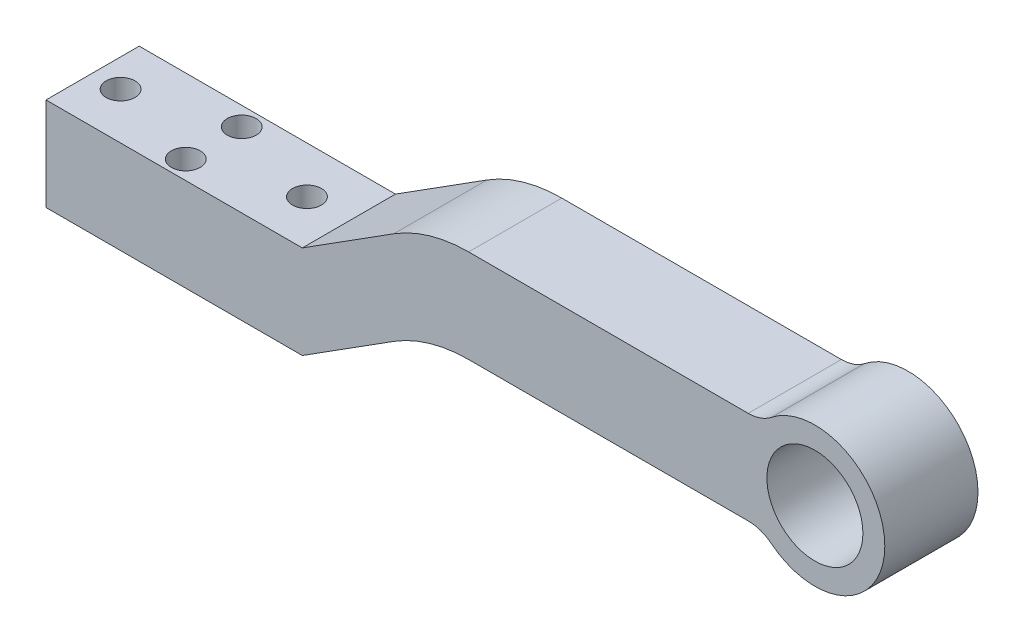
SolidWorks part; units mm, degrees
ref_plane "前视基准面" through (0, 0, 0) normal (0, 0, 1) x (1, 0, 0)
ref_plane "上视基准面" through (0, 0, 0) normal (0, 1, 0) x (1, 0, 0)
ref_plane "右视基准面" through (0, 0, 0) normal (1, 0, 0) x (0, 0, -1)
sketch "Model" plane through (0, 0, 0) normal (0, 0, 1) x (1, 0, 0)
  line L0 (233.5911, 295.2839) -> (226.2378, 290.6239)
  line L1 (168.2378, 270.6239) -> (226.2378, 270.6239)
  line L2 (261.9279, 287.7249) -> (321.9187, 287.7249)
  line L3 (261.9282, 307.7249) -> (321.9201, 307.724)
  line L4 (168.2378, 290.6239) -> (217.5323, 290.6239)
  line L5 (168.2378, 290.6239) -> (168.2378, 270.6239)
  line L6 (245.8692, 283.0649) -> (226.2378, 270.6239)
  line L7 (245.8691, 303.0649) -> (233.5911, 295.2839)
  line L8 (217.5323, 290.6239) -> (226.2378, 290.6239)
  arc A0 (326.8993, 285.9854) -> (326.9002, 309.4631) centre (336.2378, 297.7239) ccw
  arc A1 (326.8993, 285.9854) -> (321.9187, 287.7249) centre (321.9187, 279.7249) ccw
  arc A2 (321.9201, 307.724) -> (326.9002, 309.4631) centre (321.9201, 315.724) ccw
  circle A3 centre (336.2378, 297.7239) radius 10.3
  arc A4 (261.9282, 307.7249) -> (245.8691, 303.0649) centre (261.9278, 277.7249) ccw
  arc A6 (261.9279, 287.7249) -> (245.8692, 283.0649) centre (261.9279, 257.7249) ccw
extrude "凸台-拉伸1" add sketch "Model" along normal blind 20
sketch "草图2" plane through (0, 270.6239, 0) normal (0, -1, 0) x (-1, 0, 0)
  line L0 (-168.2378, -10) -> (-226.2378, -10) construction
  line L1 (-168.2378, -20) -> (-168.2378, 0) construction
  line L2 (-226.2378, -20) -> (-226.2378, 0) construction
  circle A0 centre (-177.2378, -10) radius 1.6
  circle A1 centre (-217.2378, -10) radius 1.6
  circle A2 centre (-197.2378, -16) radius 1.6
  circle A3 centre (-197.2378, -4) radius 1.6
  point P14 (0, 0)
  point P15 (0, 0)
  dimension "D1" = 3.2
  dimension "D2" = 3.2
  dimension "D3" = 3.2
  dimension "D4" = 3.2
  dimension "D5" = 40
  dimension "D6" = 9
  dimension "D7" = 6
  dimension "D8" = 6
extrude "切除-拉伸1" cut sketch "草图2" against normal blind 22
sketch "草图4" plane through (0, 290.6239, 0) normal (0, 1, 0) x (1, 0, 0)
  circle A0 centre (177.2378, -10) radius 3.1
  circle A1 centre (197.2378, -16) radius 3.1
  circle A2 centre (197.2378, -4) radius 3.1
  circle A3 centre (217.2378, -10) radius 3.1
  dimension "D1" = 6.2
  dimension "D2" = 6.2
  dimension "D3" = 6.2
  dimension "D4" = 6.2
extrude "切除-拉伸2" cut sketch "草图4" against normal blind 9
sketch "草图5" plane through (0, 290.6239, 0) normal (0, 1, 0) x (1, 0, 0)
  line L0 (168.2378, -20) -> (171.2378, -20)
  line L1 (226.2378, -20) -> (168.2378, -20) construction
  line L2 (171.2378, -20) -> (171.2378, 0)
  line L3 (226.2378, 0) -> (168.2378, 0) construction
  line L4 (171.2378, 0) -> (168.2378, 0)
  line L5 (168.2378, 0) -> (168.2378, -20)
extrude "切除-拉伸3" cut sketch "草图5" against normal blind 22
